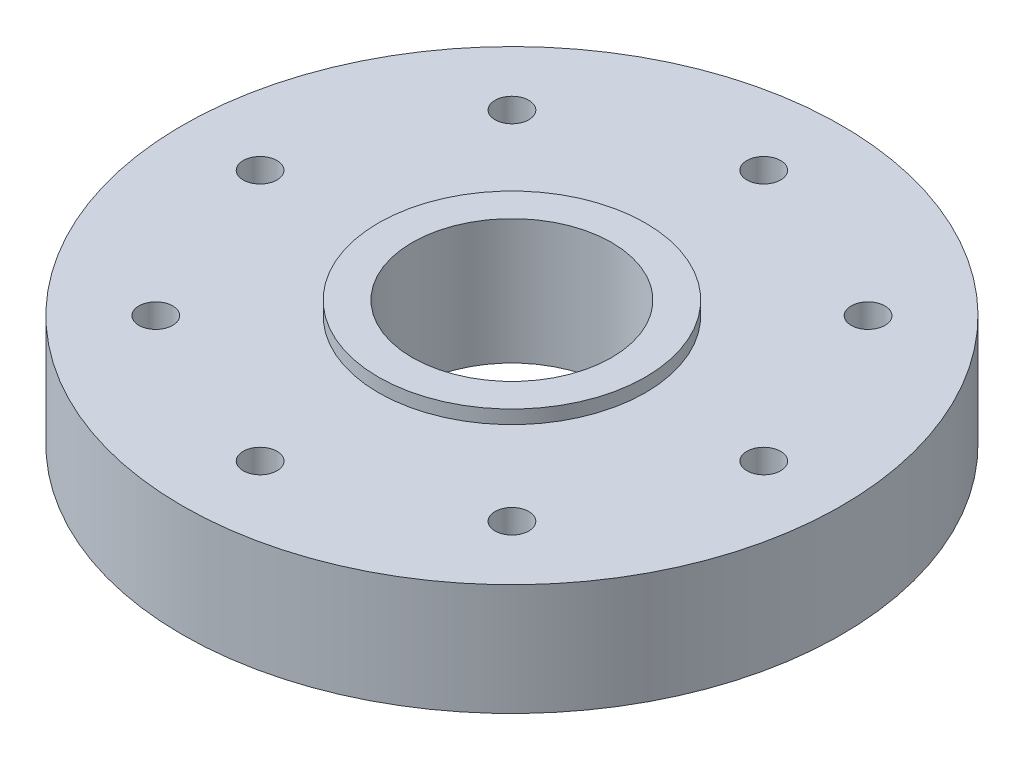
SolidWorks part; units mm, degrees
ref_plane "Front Plane" through (0, 0, 0) normal (0, 0, 1) x (1, 0, 0)
ref_plane "Top Plane" through (0, 0, 0) normal (0, 1, 0) x (1, 0, 0)
ref_plane "Right Plane" through (0, 0, 0) normal (1, 0, 0) x (0, 0, -1)
sketch "Sketch1" plane through (0, 0, 0) normal (0, 1, 0) x (1, 0, 0)
  line L0 (0, 9.75) -> (0, 7.45) construction
  circle A0 centre (0, 0) radius 9.75
  circle A1 centre (0, 0) radius 2.95
  circle A2 centre (0, 7.45) radius 0.5
  circle A3 centre (5.2679, 5.2679) radius 0.5
  circle A4 centre (7.45, 0) radius 0.5
  circle A5 centre (5.2679, -5.2679) radius 0.5
  circle A6 centre (0, -7.45) radius 0.5
  circle A7 centre (-5.2679, -5.2679) radius 0.5
  circle A8 centre (-7.45, 0) radius 0.5
  circle A9 centre (-5.2679, 5.2679) radius 0.5
  point P16 (0, 0)
  dimension "D1" = 8
extrude "Boss-Extrude1" add sketch "Sketch1" along normal blind 3.3
sketch "Sketch2" plane through (0, 3.3, 0) normal (0, 1, 0) x (1, 0, 0)
  circle A0 centre (0, 0) radius 3.95
  circle A1 centre (0, 0) radius 2.95
extrude "Boss-Extrude2" add sketch "Sketch2" along normal blind 0.4
